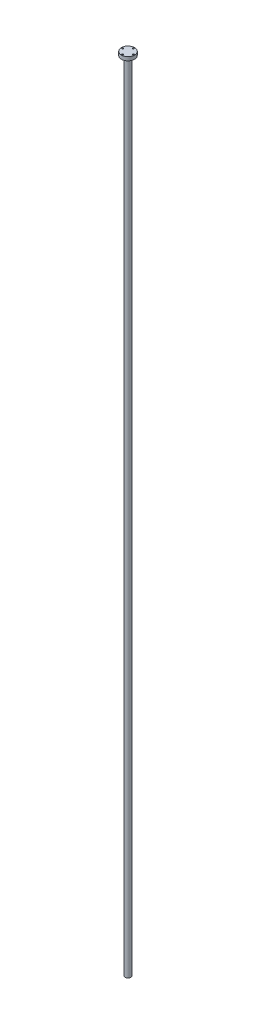
SolidWorks part; units mm, degrees
ref_plane "Front Plane" through (0, 0, 0) normal (0, 0, 1) x (1, 0, 0)
ref_plane "Top Plane" through (0, 0, 0) normal (0, 1, 0) x (1, 0, 0)
ref_plane "Right Plane" through (0, 0, 0) normal (1, 0, 0) x (0, 0, -1)
sketch "Sketch1" plane through (0, 0, 0) normal (0, 1, 0) x (1, 0, 0)
  circle A0 centre (0, 0) radius 9
  dimension "D1" = 18
extrude "BracketMount" add sketch "Sketch1" along normal blind 5
sketch "Sketch2" plane through (0, 5, 0) normal (0, 1, 0) x (1, 0, 0)
  circle A0 centre (0, 7.25) radius 1
  circle A7 centre (7.25, 0) radius 1
  circle A8 centre (0, -7.25) radius 1
  circle A9 centre (-7.25, 0) radius 1
  point P19 (0, 0)
  dimension "D1" = 2
  dimension "D3" = 7.25
  dimension "D2" = 4
extrude "Bracket-MountHoles" cut sketch "Sketch2" against normal up to surface (5 mm away) up to face at (0, 0, 9)
sketch "Sketch3" plane through (0, 0, 0) normal (0, -1, 0) x (1, 0, 0)
  circle A0 centre (0, 0) radius 4
  dimension "D1" = 8
extrude "StepperSleeve" add sketch "Sketch3" along normal blind 1094
sketch "Sketch5" plane through (0, -1094, 0) normal (0, -1, 0) x (1, 0, 0)
  line L3 (1.92, 1.7532) -> (1.92, -1.7532)
  circle A0 centre (0, 0) radius 4 construction
  arc A6 (1.92, 1.7532) -> (1.92, -1.7532) centre (0, 0) ccw
  point P7 (-2.6, 0)
  dimension "D2" = 2.6
  dimension "D1" = 4.52
extrude "OrientationNub" cut sketch "Sketch5" against normal up to surface (1094 mm away) up to face at (0, 0, 4)
equation "\"D1@StepperSleeve\"=218.8*0.5cm"
